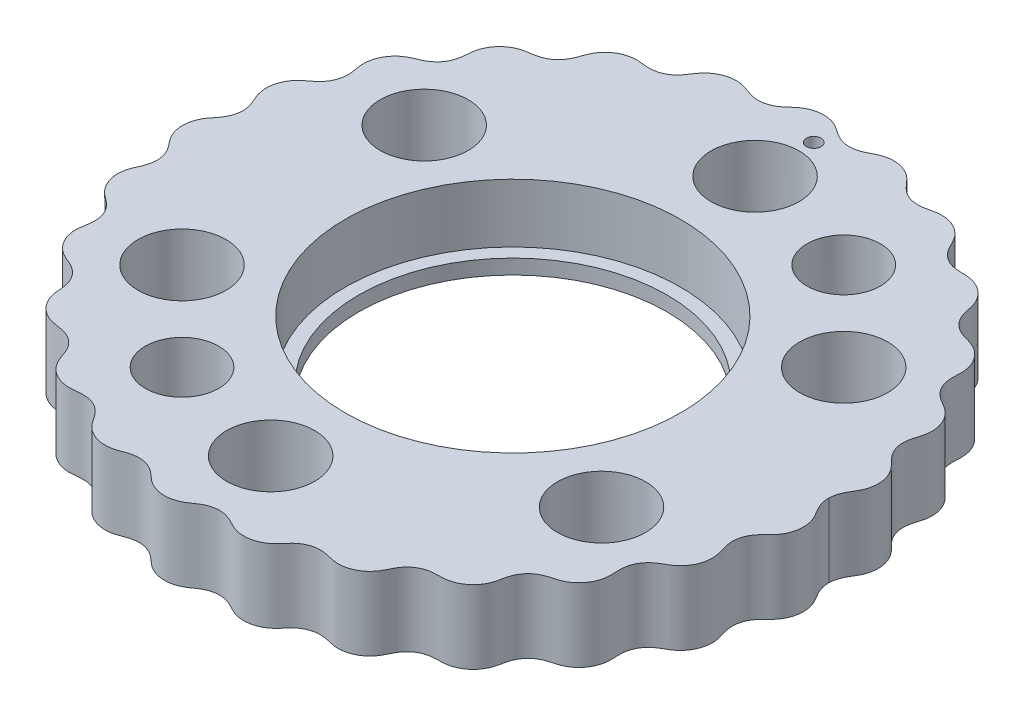
SolidWorks part; units mm, degrees
material "Like ABS"
ref_plane "Front Plane" through (0, 0, 0) normal (0, 0, 1) x (1, 0, 0)
ref_plane "Top Plane" through (0, 0, 0) normal (0, 1, 0) x (1, 0, 0)
ref_plane "Right Plane" through (0, 0, 0) normal (1, 0, 0) x (0, 0, -1)
sketch "Sketch1" plane through (0, 0, 0) normal (0, 1, 0) x (1, 0, 0)
  spline S0 degree 4 poles (18.6029, 11.2545) (18.6075, 11.136) (18.6309, 10.8996) (18.7179, 10.5625) (18.9374, 10.1618) (19.2203, 9.8531) (19.5263, 9.6277) (19.8338, 9.4559) (20.1167, 9.2925) (20.3955, 9.0753) (20.6516, 8.7949) (20.9212, 8.3592) (21.0701, 7.871) (21.0935, 7.3941) (21.0151, 6.9603) (20.9268, 6.6713) (20.827, 6.3532) (20.7583, 5.9932) (20.7579, 5.5953) (20.855, 5.178) (21.0326, 4.8178) (21.2602, 4.5208) (21.5076, 4.2761) (21.7427, 4.0542) (21.9657, 3.7863) (22.1537, 3.4641) (22.3225, 2.9952) (22.3687, 2.5028) (22.3031, 2.0452) (22.1511, 1.6464) (22.0285, 1.4194) (21.9119, 1.2324) (21.8067, 1.0573) (21.7163, 0.8934) (21.6305, 0.703) (21.5677, 0.5145) (21.5301, 0.3455) (21.5114, 0.2182) (21.5031, 0.1178) (21.4994, 0.0196) (21.5, -0.0455) (21.5057, -0.1633) (21.518, -0.2671) (21.5363, -0.3716) (21.5605, -0.4763) (21.5978, -0.6046) (21.6488, -0.7429) (21.7155, -0.8894) (21.7983, -1.0429) (21.8809, -1.1813) (21.9656, -1.3183) (22.0477, -1.4571) (22.1416, -1.6354) (22.2863, -1.9816) (22.3684, -2.421) (22.3358, -2.9349) (22.1741, -3.4197) (21.991, -3.7495) (21.772, -4.0233) (21.539, -4.2475) (21.2876, -4.4904) (21.0523, -4.786) (20.8663, -5.1459) (20.7615, -5.5648) (20.7557, -5.9689) (20.8225, -6.3389) (20.9266, -6.6708) (21.0208, -6.9784) (21.0782, -7.3225) (21.0775, -7.6978) (21.0031, -8.0938) (20.8436, -8.4925) (20.6233, -8.8316) (20.3625, -9.1053) (20.0808, -9.3156) (19.7984, -9.4746) (19.4941, -9.6484) (19.193, -9.8781) (18.9224, -10.185) (18.7166, -10.5727) (18.6147, -10.9677) (18.5925, -11.3426) (18.6115, -11.683) (18.6241, -11.9911) (18.5951, -12.3311) (18.5028, -12.6932) (18.3324, -13.0606) (18.0751, -13.4116) (17.7743, -13.6867) (17.4523, -13.8864) (17.126, -14.0192) (16.8121, -14.1026) (16.4734, -14.1962) (16.1245, -14.3457) (15.7808, -14.582) (15.4788, -14.9208) (15.2835, -15.2936) (15.1749, -15.6637) (15.1113, -15.9998) (15.0432, -16.2929) (14.9273, -16.6033) (14.7486, -16.9176) (14.4956, -17.2208) (14.1638, -17.4903) (13.8066, -17.6794) (13.4438, -17.7919) (13.0938, -17.8383) (12.7683, -17.8404) (12.4162, -17.8477) (12.0403, -17.9075) (11.6491, -18.0533) (11.2738, -18.3086) (10.994, -18.6222) (10.7986, -18.9537) (10.654, -19.2627) (10.5146, -19.5288) (10.3249, -19.7991) (10.0732, -20.058) (9.7528, -20.2872) (9.3635, -20.4656) (8.8909, -20.5765) (8.4239, -20.5773) (8.0011, -20.4727) (7.5788, -20.3726) (7.1982, -20.3396) (6.7831, -20.3853) (6.3568, -20.5422) (6.0096, -20.7778) (5.7397, -21.0508) (5.5235, -21.3136) (5.3222, -21.5355) (5.0709, -21.7488) (4.7631, -21.9354) (4.2941, -22.1159) (3.7831, -22.1727) (3.2971, -22.1042) (2.8667, -21.9331) (2.5797, -21.7766) (2.2654, -21.614) (1.9042, -21.4879) (1.4895, -21.4317) (1.0382, -21.4801) (0.6443, -21.6241) (0.3167, -21.822) (0.0427, -22.0226) (-0.2074, -22.1862) (-0.5976, -22.3746) (-1.0573, -22.4797) (-1.5638, -22.4712) (-2.0548, -22.3329) (-2.3972, -22.1622) (-2.6839, -21.9521) (-2.9229, -21.7281) (-3.1883, -21.4926) (-3.5084, -21.2816) (-3.8975, -21.126) (-4.347, -21.0633) (-4.7636, -21.107) (-5.1287, -21.2185) (-5.4432, -21.3443) (-5.7258, -21.4396) (-6.0477, -21.503) (-6.4056, -21.516) (-6.9028, -21.4457) (-7.3774, -21.2468) (-7.7696, -20.9496) (-8.0632, -20.5887) (-8.2391, -20.3115) (-8.4387, -20.0171) (-8.6983, -19.7336) (-9.0382, -19.4877) (-9.459, -19.3178) (-9.8732, -19.2589) (-10.2536, -19.2774) (-10.5887, -19.3211) (-10.8854, -19.3421) (-11.2121, -19.3225) (-11.5609, -19.2451) (-12.0244, -19.0522) (-12.4339, -18.7404) (-12.7391, -18.3536) (-12.9328, -17.9294) (-13.034, -17.6163) (-13.1553, -17.2811) (-13.3382, -16.9419) (-13.6084, -16.6204) (-13.9753, -16.3534) (-14.3622, -16.1956) (-14.7346, -16.1206) (-15.0692, -16.0797) (-15.3611, -16.0255) (-15.6715, -15.9244) (-15.9889, -15.7621) (-16.3889, -15.4591) (-16.707, -15.0543) (-16.9055, -14.6024) (-16.9861, -14.1422) (-17.0061, -13.8129) (-17.0516, -13.3486) (-17.2053, -12.8653) (-17.5221, -12.4221) (-17.9472, -12.11) (-18.2892, -11.9462) (-18.6023, -11.8239) (-18.8706, -11.6981) (-19.1448, -11.5225) (-19.4105, -11.2862) (-19.7169, -10.8984) (-19.9236, -10.4312) (-20.0056, -9.9443) (-19.9703, -9.4736) (-19.9036, -9.1351) (-19.8344, -8.6685) (-19.87, -8.1618) (-20.0706, -7.6597) (-20.4022, -7.2591) (-20.6929, -7.0172) (-20.9651, -6.8212) (-21.1925, -6.6324) (-21.4131, -6.3939) (-21.6103, -6.0991) (-21.8094, -5.647) (-21.8921, -5.1426) (-21.849, -4.6501) (-21.6959, -4.2025) (-21.5464, -3.8907) (-21.3642, -3.4543) (-21.2752, -2.9536) (-21.3478, -2.4176) (-21.5717, -1.9486) (-21.7936, -1.6436) (-22.008, -1.3867) (-22.1801, -1.1472) (-22.3332, -0.8616) (-22.4495, -0.5273) (-22.5298, -0.0326) (-22.4807, 0.4807) (-22.3113, 0.9462) (-22.0028, 1.4061) (-21.7069, 1.7352) (-21.4589, 2.1409) (-21.3173, 2.6263) (-21.2993, 3.0795) (-21.3816, 3.487) (-21.5215, 3.836) (-21.6648, 4.1376) (-21.7709, 4.412) (-21.8468, 4.7263) (-21.8752, 5.0782) (-21.8287, 5.5771) (-21.6522, 6.0617) (-21.3708, 6.4704) (-20.9554, 6.8384) (-20.5863, 7.0843) (-20.2459, 7.418) (-19.9902, 7.8549) (-19.8626, 8.2901) (-19.8431, 8.7048) (-19.8931, 9.0765) (-19.9566, 9.4036) (-19.99, 9.6951) (-19.9844, 10.0179) (-19.9234, 10.3644) (-19.7778, 10.7686) (-19.5075, 11.197) (-19.1432, 11.548) (-18.707, 11.7881) (-18.2921, 11.9415) (-17.9411, 12.1158) (-17.615, 12.3592) (-17.3407, 12.6771) (-17.1131, 13.113) (-16.9964, 13.6606) (-17.0054, 14.3306) (-16.7364, 15.0616) (-16.2913, 15.5744) (-15.7979, 15.8786) (-15.396, 16.016) (-15.1079, 16.0745) (-14.7772, 16.1149) (-14.408, 16.1828) (-14.0197, 16.33) (-13.6456, 16.5864) (-13.3098, 16.965) (-13.0983, 17.3919) (-12.9786, 17.8186) (-12.7567, 18.327) (-12.3913, 18.8027) (-11.8998, 19.1399) (-11.3468, 19.3098) (-10.9215, 19.3419) (-10.6278, 19.3257) (-10.3528, 19.2899) (-10.0923, 19.2689) (-9.79, 19.2729) (-9.4538, 19.3259) (-9.0826, 19.4637) (-8.6653, 19.7489) (-8.3568, 20.1103) (-8.1354, 20.4932) (-7.7931, 20.9281) (-7.4026, 21.2327) (-6.9296, 21.4377) (-6.4342, 21.5139) (-6.0801, 21.5062) (-5.761, 21.4486) (-5.4799, 21.3585) (-5.1691, 21.234) (-4.8101, 21.1175) (-4.2947, 21.0501) (-3.7627, 21.1476) (-3.3145, 21.3875) (-2.9563, 21.6957) (-2.706, 21.934) (-2.3276, 22.2175) (-1.8725, 22.4102) (-1.3673, 22.487) (-0.8758, 22.437) (-0.5342, 22.3403) (-0.2392, 22.2038) (0.0107, 22.0455) (0.2812, 21.8471) (0.6018, 21.6456) (1.0852, 21.4547) (1.7135, 21.4142) (2.2854, 21.5972) (2.7601, 21.8887) (3.2776, 22.0998) (3.7655, 22.1719) (4.2739, 22.1193) (4.7371, 21.9474) (5.0441, 21.7674) (5.2958, 21.5605) (5.4982, 21.3439) (5.7115, 21.0838) (5.9734, 20.8092) (6.402, 20.5019) (6.9217, 20.3384) (7.4286, 20.3423) (7.8839, 20.4428) (8.2031, 20.5253) (8.6655, 20.5905) (9.1564, 20.541) (9.6395, 20.3632) (10.0511, 20.076) (10.3034, 19.824) (10.4954, 19.5596) (10.637, 19.2985) (10.7794, 18.9927) (10.9663, 18.6617) (11.2365, 18.3428) (11.6043, 18.077) (11.9937, 17.92) (12.3726, 17.8514) (12.7287, 17.8398) (13.0575, 17.8402) (13.5204, 17.7867) (13.9824, 17.6156) (14.4052, 17.3223) (14.7317, 16.9409) (14.9129, 16.6326) (15.0323, 16.3277) (15.1038, 16.0387) (15.1659, 15.7063) (15.2662, 15.3387) (15.4509, 14.9631) (15.7431, 14.6159) (16.0823, 14.3692) (16.4321, 14.2105) (16.7735, 14.1119) (17.0913, 14.0302) (17.5249, 13.8621) (17.9284, 13.5808) (18.2639, 13.1907) (18.4841, 12.7394) (18.5822, 12.3946) (18.621, 12.0687) (18.6175, 11.7703) (18.595, 11.4321) (18.6023, 11.0501) (18.69, 10.6404) (18.8892, 10.2326) (19.1578, 9.9111) (19.4576, 9.6724) (19.7634, 9.4931) (20.0501, 9.335) (20.3381, 9.1271) (20.6059, 8.8542) (20.8888, 8.4298) (21.0532, 7.9505) (21.0949, 7.4807) (21.0358, 7.0511) (20.9572, 6.7626) (20.8511, 6.4397) (20.7645, 6.0666) (20.7498, 5.6474) (20.844, 5.2034) (21.0261, 4.8267) (21.2579, 4.5228) (21.5095, 4.2743) (21.7471, 4.0499) (21.9729, 3.7768) (22.1629, 3.446) (22.3301, 2.9643) (22.3688, 2.459) (22.2909, 1.993) (22.125, 1.5913) (21.9948, 1.3636) (21.8754, 1.1738) (21.7855, 1.0192) (21.7229, 0.9018) (21.6699, 0.7888) (21.6258, 0.6809) (21.5876, 0.571) (21.5558, 0.4582) (21.5339, 0.3595) (21.5196, 0.2744) (21.5104, 0.198) (21.5049, 0.135) (21.5, 0.0567) (21.4996, -0.0017) (21.5018, -0.1012) (21.5095, -0.1957) (21.52, -0.278) (21.5372, -0.3768) (21.5635, -0.4882) (21.5962, -0.5972) (21.6446, -0.7314) (21.7208, -0.903) (21.8329, -1.1074) (21.9824, -1.3413) (22.1279, -1.5977) (22.29, -1.9928) (22.3678, -2.4527) (22.3316, -2.9539) (22.1699, -3.4295) (21.9869, -3.7545) (21.7737, -4.0201) (21.5527, -4.235) (21.3073, -4.4702) (21.0701, -4.7589) (20.8765, -5.1175) (20.7635, -5.5432) (20.754, -5.9559) (20.8209, -6.3344) (20.9276, -6.6735) (21.0237, -6.9882) (21.08, -7.3402) (21.0755, -7.7242) (20.9743, -8.2226) (20.75, -8.681) (20.4407, -9.0464) (20.0199, -9.3618) (19.6438, -9.5512) (19.2696, -9.7988) (18.8657, -10.2421) (18.6796, -10.6464) (18.6183, -10.9774) (18.6053, -11.2049) knots 0 0 0 0 0 0.002701 0.005401 0.007852 0.010303 0.012162 0.01402 0.015879 0.017738 0.020183 0.022628 0.027478 0.029198 0.030919 0.032639 0.034359 0.036796 0.039233 0.041633 0.044032 0.045873 0.047715 0.049556 0.051397 0.053785 0.056173 0.060839 0.062515 0.06419 0.065866 0.066703 0.067541 0.06884 0.070138 0.071436 0.072085 0.072735 0.073159 0.073583 0.074192 0.074801 0.075411 0.07602 0.076629 0.077238 0.078456 0.079374 0.080292 0.08121 0.082128 0.083046 0.083964 0.0858 0.090659 0.093093 0.095528 0.097369 0.09921 0.101051 0.102892 0.105333 0.107775 0.110206 0.112638 0.114469 0.1163 0.118132 0.119963 0.122386 0.12481 0.12725 0.129691 0.131536 0.133381 0.135227 0.137072 0.139519 0.141967 0.144472 0.146978 0.148733 0.150488 0.152242 0.153997 0.156479 0.158961 0.161407 0.163853 0.165702 0.167552 0.169401 0.171251 0.173704 0.176158 0.178823 0.181488 0.183199 0.184911 0.186622 0.188334 0.190723 0.193111 0.195563 0.198015 0.199869 0.201722 0.203576 0.205429 0.207889 0.210349 0.213008 0.215667 0.217374 0.219082 0.220789 0.222496 0.224879 0.227262 0.22972 0.232177 0.235893 0.23775 0.239608 0.242074 0.244541 0.247193 0.249845 0.251549 0.253252 0.254955 0.256659 0.259036 0.261413 0.266339 0.268201 0.270063 0.271925 0.273787 0.276259 0.278732 0.281378 0.284024 0.285723 0.287422 0.289122 0.290821 0.295564 0.298032 0.300501 0.302367 0.304233 0.3061 0.307966 0.310444 0.312923 0.315563 0.318202 0.319898 0.321593 0.323288 0.324983 0.327349 0.329714 0.334663 0.336534 0.338404 0.340274 0.342144 0.344629 0.347114 0.349748 0.352381 0.354072 0.355763 0.357454 0.359146 0.361505 0.363865 0.368826 0.3707 0.372574 0.374449 0.376323 0.378814 0.381305 0.383932 0.386559 0.388246 0.389933 0.391621 0.393308 0.395662 0.398016 0.402988 0.404866 0.406745 0.408623 0.410502 0.415496 0.418117 0.420737 0.42242 0.424103 0.425787 0.42747 0.429818 0.432167 0.436982 0.438947 0.440912 0.442877 0.444842 0.449687 0.452301 0.454914 0.456594 0.458273 0.459953 0.461632 0.463975 0.466317 0.471143 0.473113 0.475082 0.477052 0.479021 0.483878 0.486485 0.489092 0.490767 0.492443 0.494118 0.495794 0.498131 0.500468 0.505475 0.507365 0.509256 0.513038 0.515553 0.518068 0.520669 0.523269 0.524941 0.526613 0.528284 0.529956 0.532287 0.534618 0.539637 0.541532 0.543426 0.547216 0.549737 0.552259 0.554853 0.557447 0.559114 0.560782 0.56245 0.564118 0.566443 0.568769 0.572172 0.575575 0.5778 0.580025 0.58225 0.584475 0.587001 0.589527 0.593322 0.597118 0.602145 0.606799 0.608468 0.610137 0.611805 0.613474 0.61607 0.618666 0.621185 0.623705 0.627493 0.629386 0.63128 0.636295 0.640961 0.642634 0.644306 0.645979 0.647652 0.648953 0.650254 0.652856 0.65537 0.657884 0.661663 0.663553 0.665442 0.670446 0.672784 0.675123 0.676799 0.678476 0.680152 0.681829 0.684438 0.687047 0.6919 0.693868 0.695837 0.697805 0.699773 0.704597 0.706941 0.709285 0.710965 0.712646 0.714326 0.716007 0.718622 0.721238 0.726079 0.730007 0.731971 0.733935 0.738747 0.741097 0.743447 0.745131 0.746815 0.7485 0.750184 0.752806 0.755428 0.760419 0.762297 0.764174 0.766052 0.767929 0.772898 0.775253 0.777609 0.779297 0.780986 0.782674 0.784362 0.786991 0.789619 0.792109 0.794598 0.796471 0.798345 0.800218 0.802091 0.807049 0.80941 0.811771 0.813464 0.815156 0.816848 0.81854 0.821175 0.82381 0.826294 0.828777 0.830646 0.832515 0.834384 0.836253 0.841199 0.843566 0.845934 0.84763 0.849326 0.851022 0.852719 0.85536 0.858001 0.860479 0.862956 0.864821 0.866686 0.868551 0.870415 0.872883 0.87535 0.880096 0.881796 0.883497 0.885197 0.886897 0.889545 0.892193 0.894664 0.897134 0.898995 0.900856 0.902717 0.904578 0.907039 0.909501 0.914258 0.915963 0.917667 0.919371 0.920224 0.921076 0.921739 0.922403 0.923066 0.92373 0.924393 0.925057 0.925389 0.92572 0.926052 0.926384 0.927237 0.927561 0.927886 0.928536 0.929185 0.929835 0.930484 0.931134 0.932433 0.934109 0.935786 0.937463 0.939139 0.943809 0.946282 0.948755 0.950509 0.952263 0.954018 0.955772 0.958256 0.960739 0.963224 0.965709 0.967581 0.969454 0.971326 0.973198 0.975675 0.978152 0.982844 0.984651 0.986458 0.990073 0.992435 0.994797 1 1 1 1 1 construction
  spline S1 degree 4 poles (21.5, 0) (21.5, -0.0228) (21.501, -0.0677) (21.5057, -0.1633) (21.518, -0.2671) (21.5363, -0.3716) (21.5605, -0.4763) (21.5978, -0.6046) (21.6488, -0.7429) (21.7155, -0.8894) (21.7983, -1.0429) (21.8809, -1.1813) (21.9656, -1.3183) (22.0477, -1.4571) (22.1416, -1.6354) (22.2863, -1.9816) (22.3684, -2.421) (22.3358, -2.9349) (22.1741, -3.4197) (21.991, -3.7495) (21.772, -4.0233) (21.539, -4.2475) (21.2876, -4.4904) (21.0523, -4.786) (20.8663, -5.1459) (20.7615, -5.5648) (20.7557, -5.9689) (20.8225, -6.3389) (20.9266, -6.6708) (21.0208, -6.9784) (21.0782, -7.3225) (21.0775, -7.6978) (21.0031, -8.0938) (20.8436, -8.4925) (20.6233, -8.8316) (20.3625, -9.1053) (20.0808, -9.3156) (19.7984, -9.4746) (19.4941, -9.6484) (19.193, -9.8781) (18.9224, -10.185) (18.7166, -10.5727) (18.6147, -10.9677) (18.5925, -11.3426) (18.6115, -11.683) (18.6241, -11.9911) (18.5951, -12.3311) (18.5028, -12.6932) (18.3324, -13.0606) (18.0751, -13.4116) (17.7743, -13.6867) (17.4523, -13.8864) (17.126, -14.0192) (16.8121, -14.1026) (16.4734, -14.1962) (16.1245, -14.3457) (15.7808, -14.582) (15.4788, -14.9208) (15.2835, -15.2936) (15.1749, -15.6637) (15.1113, -15.9998) (15.0432, -16.2929) (14.9273, -16.6033) (14.7486, -16.9176) (14.4956, -17.2208) (14.1638, -17.4903) (13.8066, -17.6794) (13.4438, -17.7919) (13.0938, -17.8383) (12.7683, -17.8404) (12.4162, -17.8477) (12.0403, -17.9075) (11.6491, -18.0533) (11.2738, -18.3086) (10.994, -18.6222) (10.7986, -18.9537) (10.654, -19.2627) (10.5146, -19.5288) (10.3249, -19.7991) (10.0732, -20.058) (9.7528, -20.2872) (9.3635, -20.4656) (8.8909, -20.5765) (8.4239, -20.5773) (8.0011, -20.4727) (7.5788, -20.3726) (7.1982, -20.3396) (6.7831, -20.3853) (6.3568, -20.5422) (6.0096, -20.7778) (5.7397, -21.0508) (5.5235, -21.3136) (5.3222, -21.5355) (5.0709, -21.7488) (4.7631, -21.9354) (4.2941, -22.1159) (3.7831, -22.1727) (3.2971, -22.1042) (2.8667, -21.9331) (2.5797, -21.7766) (2.2654, -21.614) (1.9042, -21.4879) (1.4895, -21.4317) (1.0382, -21.4801) (0.6443, -21.6241) (0.3167, -21.822) (0.0427, -22.0226) (-0.2074, -22.1862) (-0.5976, -22.3746) (-1.0573, -22.4797) (-1.5638, -22.4712) (-2.0548, -22.3329) (-2.3972, -22.1622) (-2.6839, -21.9521) (-2.9229, -21.7281) (-3.1883, -21.4926) (-3.5084, -21.2816) (-3.8975, -21.126) (-4.347, -21.0633) (-4.7636, -21.107) (-5.1287, -21.2185) (-5.4432, -21.3443) (-5.7258, -21.4396) (-6.0477, -21.503) (-6.4056, -21.516) (-6.9028, -21.4457) (-7.3774, -21.2468) (-7.7696, -20.9496) (-8.0632, -20.5887) (-8.2391, -20.3115) (-8.4387, -20.0171) (-8.6983, -19.7336) (-9.0382, -19.4877) (-9.459, -19.3178) (-9.8732, -19.2589) (-10.2536, -19.2774) (-10.5887, -19.3211) (-10.8854, -19.3421) (-11.2121, -19.3225) (-11.5609, -19.2451) (-12.0244, -19.0522) (-12.4339, -18.7404) (-12.7391, -18.3536) (-12.9328, -17.9294) (-13.034, -17.6163) (-13.1553, -17.2811) (-13.3382, -16.9419) (-13.6084, -16.6204) (-13.9753, -16.3534) (-14.3622, -16.1956) (-14.7346, -16.1206) (-15.0692, -16.0797) (-15.3611, -16.0255) (-15.6715, -15.9244) (-15.9889, -15.7621) (-16.3889, -15.4591) (-16.707, -15.0543) (-16.9055, -14.6024) (-16.9861, -14.1422) (-17.0061, -13.8129) (-17.0516, -13.3486) (-17.2053, -12.8653) (-17.5221, -12.4221) (-17.9472, -12.11) (-18.2892, -11.9462) (-18.6023, -11.8239) (-18.8706, -11.6981) (-19.1448, -11.5225) (-19.4105, -11.2862) (-19.7169, -10.8984) (-19.9236, -10.4312) (-20.0056, -9.9443) (-19.9703, -9.4736) (-19.9036, -9.1351) (-19.8344, -8.6685) (-19.87, -8.1618) (-20.0706, -7.6597) (-20.4022, -7.2591) (-20.6929, -7.0172) (-20.9651, -6.8212) (-21.1925, -6.6324) (-21.4131, -6.3939) (-21.6103, -6.0991) (-21.8094, -5.647) (-21.8921, -5.1426) (-21.849, -4.6501) (-21.6959, -4.2025) (-21.5464, -3.8907) (-21.3642, -3.4543) (-21.2752, -2.9536) (-21.3478, -2.4176) (-21.5717, -1.9486) (-21.7936, -1.6436) (-22.008, -1.3867) (-22.1801, -1.1472) (-22.3332, -0.8616) (-22.4495, -0.5273) (-22.5298, -0.0326) (-22.4807, 0.4807) (-22.3113, 0.9462) (-22.0028, 1.4061) (-21.7069, 1.7352) (-21.4589, 2.1409) (-21.3173, 2.6263) (-21.2993, 3.0795) (-21.3816, 3.487) (-21.5215, 3.836) (-21.6648, 4.1376) (-21.7709, 4.412) (-21.8468, 4.7263) (-21.8752, 5.0782) (-21.8287, 5.5771) (-21.6522, 6.0617) (-21.3708, 6.4704) (-20.9554, 6.8384) (-20.5863, 7.0843) (-20.2459, 7.418) (-19.9902, 7.8549) (-19.8626, 8.2901) (-19.8431, 8.7048) (-19.8931, 9.0765) (-19.9566, 9.4036) (-19.99, 9.6951) (-19.9844, 10.0179) (-19.9234, 10.3644) (-19.7778, 10.7686) (-19.5075, 11.197) (-19.1432, 11.548) (-18.707, 11.7881) (-18.2921, 11.9415) (-17.9411, 12.1158) (-17.615, 12.3592) (-17.3407, 12.6771) (-17.1131, 13.113) (-16.9964, 13.6606) (-17.0054, 14.3306) (-16.7364, 15.0616) (-16.2913, 15.5744) (-15.7979, 15.8786) (-15.396, 16.016) (-15.1079, 16.0745) (-14.7772, 16.1149) (-14.408, 16.1828) (-14.0197, 16.33) (-13.6456, 16.5864) (-13.3098, 16.965) (-13.0983, 17.3919) (-12.9786, 17.8186) (-12.7567, 18.327) (-12.3913, 18.8027) (-11.8998, 19.1399) (-11.3468, 19.3098) (-10.9215, 19.3419) (-10.6278, 19.3257) (-10.3528, 19.2899) (-10.0923, 19.2689) (-9.79, 19.2729) (-9.4538, 19.3259) (-9.0826, 19.4637) (-8.6653, 19.7489) (-8.3568, 20.1103) (-8.1354, 20.4932) (-7.7931, 20.9281) (-7.4026, 21.2327) (-6.9296, 21.4377) (-6.4342, 21.5139) (-6.0801, 21.5062) (-5.761, 21.4486) (-5.4799, 21.3585) (-5.1691, 21.234) (-4.8101, 21.1175) (-4.2947, 21.0501) (-3.7627, 21.1476) (-3.3145, 21.3875) (-2.9563, 21.6957) (-2.706, 21.934) (-2.3276, 22.2175) (-1.8725, 22.4102) (-1.3673, 22.487) (-0.8758, 22.437) (-0.5342, 22.3403) (-0.2392, 22.2038) (0.0107, 22.0455) (0.2812, 21.8471) (0.6018, 21.6456) (1.0852, 21.4547) (1.7135, 21.4142) (2.2854, 21.5972) (2.7601, 21.8887) (3.2776, 22.0998) (3.7655, 22.1719) (4.2739, 22.1193) (4.7371, 21.9474) (5.0441, 21.7674) (5.2958, 21.5605) (5.4982, 21.3439) (5.7115, 21.0838) (5.9734, 20.8092) (6.402, 20.5019) (6.9217, 20.3384) (7.4286, 20.3423) (7.8839, 20.4428) (8.2031, 20.5253) (8.6655, 20.5905) (9.1564, 20.541) (9.6395, 20.3632) (10.0511, 20.076) (10.3034, 19.824) (10.4954, 19.5596) (10.637, 19.2985) (10.7794, 18.9927) (10.9663, 18.6617) (11.2365, 18.3428) (11.6043, 18.077) (11.9937, 17.92) (12.3726, 17.8514) (12.7287, 17.8398) (13.0575, 17.8402) (13.5204, 17.7867) (13.9824, 17.6156) (14.4052, 17.3223) (14.7317, 16.9409) (14.9129, 16.6326) (15.0323, 16.3277) (15.1038, 16.0387) (15.1659, 15.7063) (15.2662, 15.3387) (15.4509, 14.9631) (15.7431, 14.6159) (16.0823, 14.3692) (16.4321, 14.2105) (16.7735, 14.1119) (17.0913, 14.0302) (17.5249, 13.8621) (17.9284, 13.5808) (18.2639, 13.1907) (18.4841, 12.7394) (18.5822, 12.3946) (18.621, 12.0687) (18.6175, 11.7703) (18.595, 11.4321) (18.6023, 11.0501) (18.69, 10.6404) (18.8892, 10.2326) (19.1578, 9.9111) (19.4576, 9.6724) (19.7634, 9.4931) (20.0501, 9.335) (20.3381, 9.1271) (20.6059, 8.8542) (20.8888, 8.4298) (21.0532, 7.9505) (21.0949, 7.4807) (21.0358, 7.0511) (20.9572, 6.7626) (20.8511, 6.4397) (20.7645, 6.0666) (20.7498, 5.6474) (20.844, 5.2034) (21.0261, 4.8267) (21.2579, 4.5228) (21.5095, 4.2743) (21.7471, 4.0499) (21.9729, 3.7768) (22.1629, 3.446) (22.3301, 2.9643) (22.3688, 2.459) (22.2909, 1.993) (22.125, 1.5913) (21.9948, 1.3636) (21.8754, 1.1738) (21.7855, 1.0192) (21.7229, 0.9018) (21.6699, 0.7888) (21.6258, 0.6809) (21.5876, 0.571) (21.5558, 0.4582) (21.5339, 0.3595) (21.5196, 0.2744) (21.5104, 0.198) (21.5049, 0.135) (21.5023, 0.0928) (21.5012, 0.0678) (21.5008, 0.0554) knots 0.073583 0.073583 0.073583 0.073583 0.073583 0.074192 0.074801 0.075411 0.07602 0.076629 0.077238 0.078456 0.079374 0.080292 0.08121 0.082128 0.083046 0.083964 0.0858 0.090659 0.093093 0.095528 0.097369 0.09921 0.101051 0.102892 0.105333 0.107775 0.110206 0.112638 0.114469 0.1163 0.118132 0.119963 0.122386 0.12481 0.12725 0.129691 0.131536 0.133381 0.135227 0.137072 0.139519 0.141967 0.144472 0.146978 0.148733 0.150488 0.152242 0.153997 0.156479 0.158961 0.161407 0.163853 0.165702 0.167552 0.169401 0.171251 0.173704 0.176158 0.178823 0.181488 0.183199 0.184911 0.186622 0.188334 0.190723 0.193111 0.195563 0.198015 0.199869 0.201722 0.203576 0.205429 0.207889 0.210349 0.213008 0.215667 0.217374 0.219082 0.220789 0.222496 0.224879 0.227262 0.22972 0.232177 0.235893 0.23775 0.239608 0.242074 0.244541 0.247193 0.249845 0.251549 0.253252 0.254955 0.256659 0.259036 0.261413 0.266339 0.268201 0.270063 0.271925 0.273787 0.276259 0.278732 0.281378 0.284024 0.285723 0.287422 0.289122 0.290821 0.295564 0.298032 0.300501 0.302367 0.304233 0.3061 0.307966 0.310444 0.312923 0.315563 0.318202 0.319898 0.321593 0.323288 0.324983 0.327349 0.329714 0.334663 0.336534 0.338404 0.340274 0.342144 0.344629 0.347114 0.349748 0.352381 0.354072 0.355763 0.357454 0.359146 0.361505 0.363865 0.368826 0.3707 0.372574 0.374449 0.376323 0.378814 0.381305 0.383932 0.386559 0.388246 0.389933 0.391621 0.393308 0.395662 0.398016 0.402988 0.404866 0.406745 0.408623 0.410502 0.415496 0.418117 0.420737 0.42242 0.424103 0.425787 0.42747 0.429818 0.432167 0.436982 0.438947 0.440912 0.442877 0.444842 0.449687 0.452301 0.454914 0.456594 0.458273 0.459953 0.461632 0.463975 0.466317 0.471143 0.473113 0.475082 0.477052 0.479021 0.483878 0.486485 0.489092 0.490767 0.492443 0.494118 0.495794 0.498131 0.500468 0.505475 0.507365 0.509256 0.513038 0.515553 0.518068 0.520669 0.523269 0.524941 0.526613 0.528284 0.529956 0.532287 0.534618 0.539637 0.541532 0.543426 0.547216 0.549737 0.552259 0.554853 0.557447 0.559114 0.560782 0.56245 0.564118 0.566443 0.568769 0.572172 0.575575 0.5778 0.580025 0.58225 0.584475 0.587001 0.589527 0.593322 0.597118 0.602145 0.606799 0.608468 0.610137 0.611805 0.613474 0.61607 0.618666 0.621185 0.623705 0.627493 0.629386 0.63128 0.636295 0.640961 0.642634 0.644306 0.645979 0.647652 0.648953 0.650254 0.652856 0.65537 0.657884 0.661663 0.663553 0.665442 0.670446 0.672784 0.675123 0.676799 0.678476 0.680152 0.681829 0.684438 0.687047 0.6919 0.693868 0.695837 0.697805 0.699773 0.704597 0.706941 0.709285 0.710965 0.712646 0.714326 0.716007 0.718622 0.721238 0.726079 0.730007 0.731971 0.733935 0.738747 0.741097 0.743447 0.745131 0.746815 0.7485 0.750184 0.752806 0.755428 0.760419 0.762297 0.764174 0.766052 0.767929 0.772898 0.775253 0.777609 0.779297 0.780986 0.782674 0.784362 0.786991 0.789619 0.792109 0.794598 0.796471 0.798345 0.800218 0.802091 0.807049 0.80941 0.811771 0.813464 0.815156 0.816848 0.81854 0.821175 0.82381 0.826294 0.828777 0.830646 0.832515 0.834384 0.836253 0.841199 0.843566 0.845934 0.84763 0.849326 0.851022 0.852719 0.85536 0.858001 0.860479 0.862956 0.864821 0.866686 0.868551 0.870415 0.872883 0.87535 0.880096 0.881796 0.883497 0.885197 0.886897 0.889545 0.892193 0.894664 0.897134 0.898995 0.900856 0.902717 0.904578 0.907039 0.909501 0.914258 0.915963 0.917667 0.919371 0.920224 0.921076 0.921739 0.922403 0.923066 0.92373 0.924393 0.925057 0.925389 0.92572 0.926052 0.926384 0.926384 0.926384 0.926384 0.926384
  spline S2 degree 1 poles (21.5008, 0.0554) (21.5, 0) knots 0 0 1 1
extrude "Boss-Extrude1" add sketch "Sketch1" along normal blind 5
sketch "Sketch2" plane through (0, 5, 0) normal (0, 1, 0) x (1, 0, 0)
  circle A0 centre (0, 0) radius 11.425
  dimension "D1" = 22.85
extrude "Cut-Extrude1" cut sketch "Sketch2" against normal up to surface (5 mm away) up to face at (21.5004, 0, -0.0277)
sketch "Sketch3" plane through (0, 5, 0) normal (0, 1, 0) x (1, 0, 0)
  line L0 (0, 0) -> (0, 16.5) construction
  circle A0 centre (0, 16.5) radius 3
  dimension "D1" = 6
  dimension "D2" = 16.5
extrude "Cut-Extrude2" cut sketch "Sketch3" against normal up to surface (5 mm away) up to face at (0, 0, -11.425)
pattern_circular "CirPattern1" count 6 over 360 about axis through (0, 0, 0) along (0, 1, 0) of "Cut-Extrude2"
sketch "Sketch5" plane through (0, 5, 0) normal (0, 1, 0) x (1, 0, 0)
  line L0 (0, 16.5) -> (0, 0) construction
  line L1 (0, 0) -> (8.25, 14.2894) construction
  circle A0 centre (8.25, 14.2894) radius 2.5
  dimension "D2" = 5
  dimension "D1" = 30
extrude "Cut-Extrude3" cut sketch "Sketch5" against normal up to surface (5 mm away) up to face at (-14.2894, 0, -11.25)
pattern_circular "CirPattern2" count 2 over 360 about axis through (0, 0, 0) along (0, 1, 0) of "Cut-Extrude3"
sketch "Sketch6" plane through (0, 5, 0) normal (0, 1, 0) x (1, 0, 0)
  line L0 (0, 0) -> (0, 20.5) construction
  circle A0 centre (0, 20.5) radius 0.5
  dimension "D2" = 1
  dimension "D1" = 20.5
extrude "Cut-Extrude4" cut sketch "Sketch6" against normal up to surface (5 mm away) up to face at (-8.25, 0, 11.7894)
sketch "Sketch7" plane through (0, 0, 0) normal (0, -1, 0) x (1, 0, 0)
  circle A0 centre (0, 0) radius 10.5
  circle A1 centre (0, 0) radius 12.3746
  dimension "D1" = 21
extrude "Boss-Extrude2" add sketch "Sketch7" against normal blind 1
